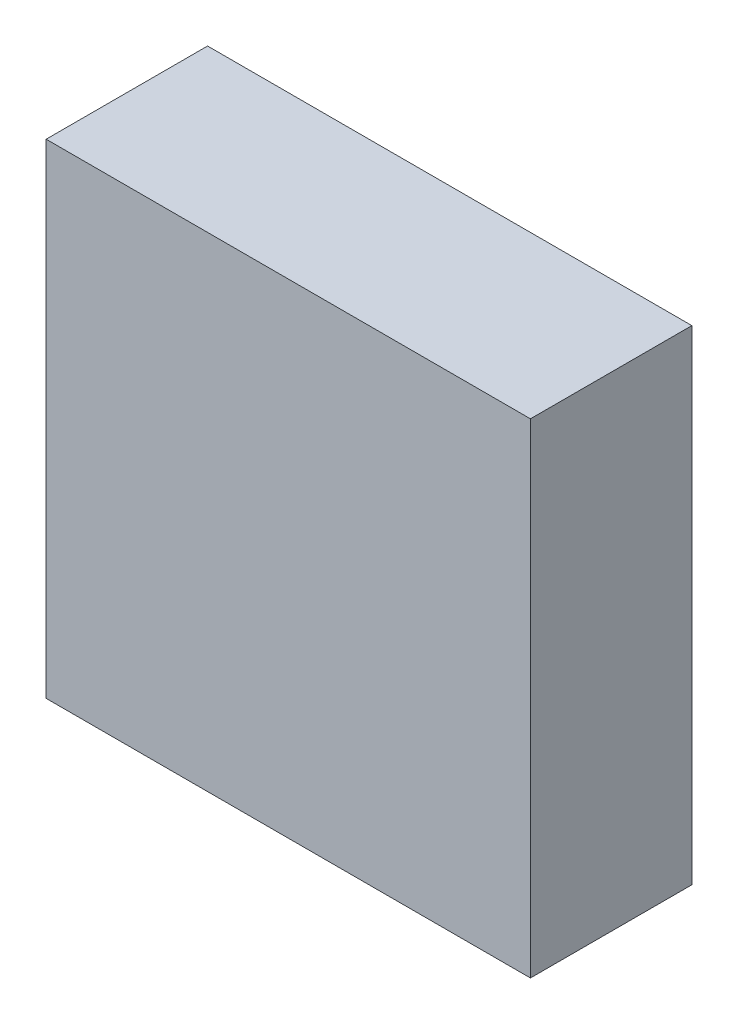
SolidWorks part; units mm, degrees
ref_plane "Front Plane" through (0, 0, 0) normal (0, 0, 1) x (1, 0, 0)
ref_plane "Top Plane" through (0, 0, 0) normal (0, 1, 0) x (1, 0, 0)
ref_plane "Right Plane" through (0, 0, 0) normal (1, 0, 0) x (0, 0, -1)
sketch "Sketch1" plane through (0, 0, 0) normal (0, 1, 0) x (1, 0, 0)
  line L0 (0, 0) -> (60, 0) construction
  line L1 (-15, 0) -> (0, 0) construction
  line L2 (-15, 15) -> (75, 15)
  line L3 (-15, 15) -> (-15, -15)
  line L4 (-15, -15) -> (75, -15)
  line L5 (75, 15) -> (75, -15)
  line L6 (60, 0) -> (75, 0) construction
  circle A0 centre (0, 0) radius 10.585
  circle A1 centre (60, 0) radius 10.585
  circle A2 centre (30, 0) radius 10.585
  point P7 (-16.298, 14.3641)
  dimension "D1" = 21.17
  dimension "D2" = 30
  dimension "D3" = 15
  dimension "D4" = 15
extrude "Boss-Extrude1" add sketch "Sketch1" along normal blind 80
sketch "Sketch2" plane through (0, 80, 0) normal (0, 1, 0) x (1, 0, 0)
  line L1 (-15, 15) -> (75, 15)
  line L2 (-15, 15) -> (-15, -15)
  line L3 (-15, -15) -> (75, -15)
  line L4 (75, 15) -> (75, -15)
  line L5 (-15, 15) -> (75, -15) construction
  line L6 (-15, -15) -> (75, 15) construction
  point P4 (30, 0)
extrude "Boss-Extrude2" add sketch "Sketch2" along normal blind 5
sketch "Sketch3" plane through (0, 0, 0) normal (0, -1, 0) x (1, 0, 0)
  line L1 (75, -15) -> (-15, -15)
  line L2 (75, -15) -> (75, 15)
  line L3 (75, 15) -> (-15, 15)
  line L4 (-15, -15) -> (-15, 15)
  line L5 (75, -15) -> (-15, 15) construction
  line L6 (75, 15) -> (-15, -15) construction
  point P4 (30, 0)
extrude "Boss-Extrude3" add sketch "Sketch3" along normal blind 5
sketch "Sketch4" plane through (0, 0, -15) normal (0, 0, -1) x (-1, 0, 0)
  line L0 (15, 85) -> (15, -5) construction
  line L1 (-70.585, 3) -> (10.585, 3)
  line L2 (-70.585, 3) -> (-70.585, 77)
  line L3 (-70.585, 77) -> (10.585, 77)
  line L4 (10.585, 3) -> (10.585, 77)
  line L5 (-70.585, 3) -> (10.585, 77) construction
  line L6 (-70.585, 77) -> (10.585, 3) construction
  line L7 (-75, 85) -> (-75, -5) construction
  line L8 (15, -5) -> (-75, -5) construction
  line L9 (-75, 85) -> (15, 85) construction
  point P4 (-30, 40)
  dimension "D1" = 4.415
  dimension "D2" = 4.415
  dimension "D3" = 8
  dimension "D4" = 8
extrude "Cut-Extrude1" cut sketch "Sketch4" against normal blind 15
sketch "Sketch5" plane through (0, 0, -15) normal (0, 0, -1) x (-1, 0, 0)
  line L0 (15, 85) -> (15, -5) construction
  line L1 (10, 1) -> (-70, 1)
  line L2 (10, 1) -> (10, 2)
  line L3 (10, 2) -> (-70, 2)
  line L4 (-70, 1) -> (-70, 2)
  line L5 (10, 1) -> (-70, 2) construction
  line L6 (10, 2) -> (-70, 1) construction
  line L7 (-75, 85) -> (-75, -5) construction
  line L8 (-70.585, 3) -> (10.585, 3) construction
  point P4 (-30, 1.5)
  dimension "D1" = 5
  dimension "D2" = 5
  dimension "D3" = 1
  dimension "D4" = 1
